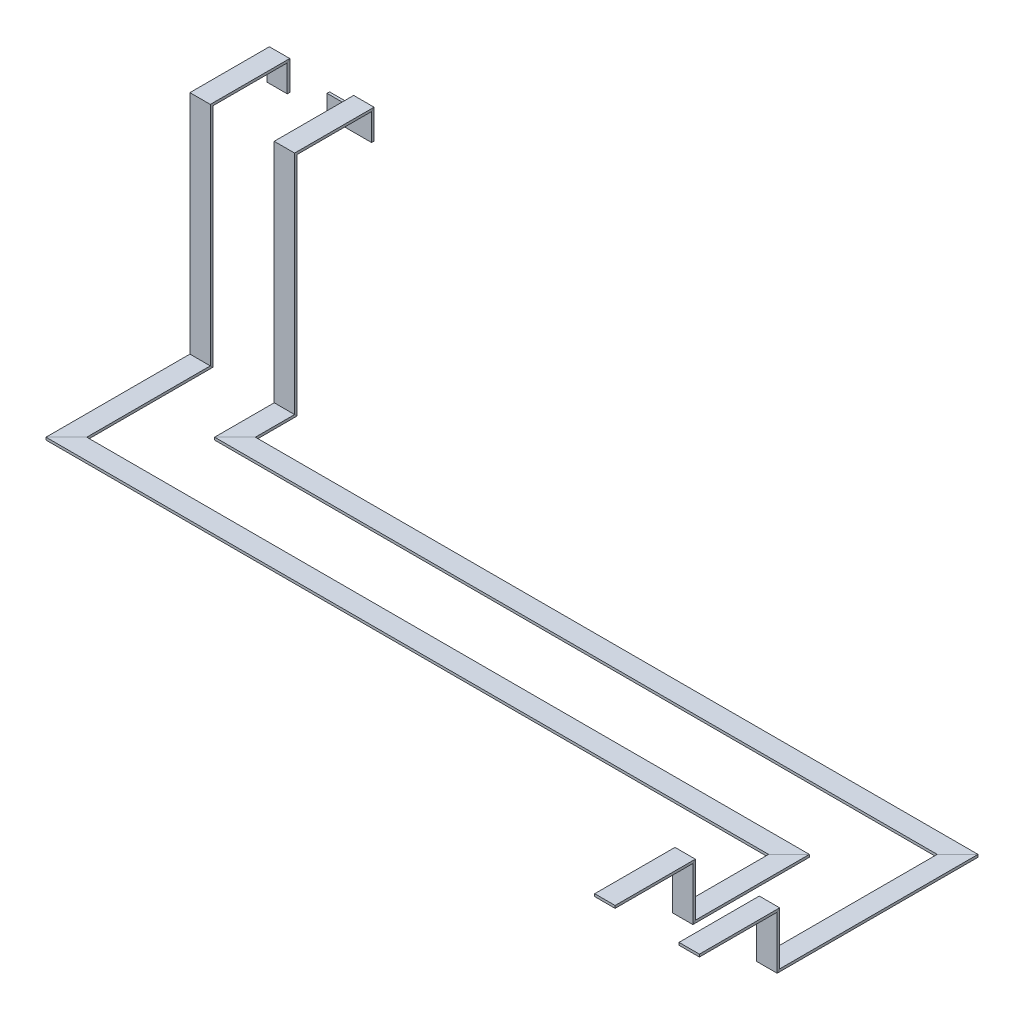
SolidWorks part; units mm, degrees
ref_plane "Alzado" through (0, 0, 0) normal (0, 0, 1) x (1, 0, 0)
ref_plane "Planta" through (0, 0, 0) normal (0, 1, 0) x (1, 0, 0)
ref_plane "Vista lateral" through (0, 0, 0) normal (1, 0, 0) x (0, 0, -1)
sketch "Croquis2" plane through (0, 0, 0) normal (0, 1, 0) x (1, 0, 0)
  line L1 (-25.4, 3.155) -> (25.4, 3.155)
  line L2 (-25.4, 3.155) -> (-25.4, -3.155)
  line L3 (-25.4, -3.155) -> (25.4, -3.155)
  line L4 (25.4, 3.155) -> (25.4, -3.155)
  line L5 (-25.4, 3.155) -> (25.4, -3.155) construction
  line L6 (-25.4, -3.155) -> (25.4, 3.155) construction
  line L7 (184.6, 3.155) -> (235.4, 3.155)
  line L8 (184.6, 3.155) -> (184.6, -3.155)
  line L9 (184.6, -3.155) -> (235.4, -3.155)
  line L10 (235.4, 3.155) -> (235.4, -3.155)
  line L11 (184.6, 3.155) -> (235.4, -3.155) construction
  line L12 (184.6, -3.155) -> (235.4, 3.155) construction
  point P0 (0, 0)
  point P6 (210, 0)
  dimension "D1" = 50.8
  dimension "D2" = 6.31
  dimension "D3" = 210
  dimension "D4" = 50.8
  dimension "D5" = 6.31
sketch3d "Croquis3D1"
  line L0 (0, 0, 0) -> (0, -567.24, 0)
  line L1 (0, -567.24, 0) -> (0, -567.24, 336.2)
  line L2 (0, -567.24, 336.2) -> (1800, -567.24, 336.2)
  line L3 (1800, -567.24, 336.2) -> (1800, -567.24, 598)
  line L4 (-25.4, 0, 0) -> (-25.4, -383.9185, 0) construction
  line L5 (-25.4, 0, -3.155) -> (-25.4, 0, 3.155) construction
  line L6 (-25.4, -383.9185, 0) -> (-25.4, -383.9185, 653.2834) construction
  line L7 (1800, -567.24, 598) -> (1800, -435.4728, 598)
  line L8 (1800, -435.4728, 598) -> (1800, -435.4728, 794.7829)
  dimension "D1" = 567.24
  dimension "D2" = 336.2
  dimension "D3" = 1800
  dimension "D4" = 261.8
  dimension "D5" = 131.7672
  dimension "D6" = 196.7829
sweep "Barrer1" add profiles "Croquis2" path "Croquis3D1"
sketch "Croquis3" plane through (0, 0, -3.155) normal (0, 0, -1) x (-1, 0, 0)
  line L0 (-235.4, 0) -> (-235.4, -6.31)
  line L1 (-235.4, 0) -> (-235.4, -570.395) construction
  line L2 (-235.4, -6.31) -> (-184.6, -6.31)
  line L3 (-184.6, 0) -> (-184.6, -570.395) construction
  line L4 (-184.6, -6.31) -> (-184.6, 0)
  line L5 (-184.6, 0) -> (-235.4, 0)
  line L7 (-25.4, 0) -> (-25.4, -6.31)
  line L8 (-25.4, 0) -> (-25.4, -570.395) construction
  line L9 (-25.4, -6.31) -> (25.4, -6.31)
  line L10 (25.4, 0) -> (25.4, -570.395) construction
  line L11 (25.4, -6.31) -> (25.4, 0)
  line L12 (-25.4, 0) -> (25.4, 0) construction
  line L13 (25.4, 0) -> (-25.4, 0)
  dimension "D1" = 6.31
  dimension "D2" = 6.31
sketch3d "Croquis3D2"
  line L0 (25.4, -3.155, -3.155) -> (-0.201, -3.155, -3.155) construction
  line L1 (25.4, 0, -3.155) -> (25.4, -6.31, -3.155) construction
  line L2 (-0.201, -3.155, -3.155) -> (-0.201, -5.2746, -3.155) construction
  line L3 (-0.201, -3.155, -3.155) -> (-0.201, -3.155, -191.675)
  line L4 (-0.201, -3.155, -191.675) -> (-0.201, -73.155, -191.675)
  dimension "D1" = 188.52
  dimension "D2" = 70
sweep "Barrer4" add profiles "Croquis3" path "Croquis3D2"
sketch "Croquis4" plane through (0, 0, -194.83) normal (0, 0, -1) x (-1, 0, 0)
  line L0 (-184.6, 0) -> (-184.6, -73.155)
  line L1 (-184.6, -73.155) -> (-124.6, -73.155)
  line L2 (-124.6, -73.155) -> (-124.6, 0)
  line L3 (-124.6, 0) -> (-184.6, 0)
  dimension "D1" = 60
sketch "Croquis6" plane through (0, -432.3178, 0) normal (0, 1, 0) x (1, 0, 0)
  circle A0 centre (1285.7, -1260.295) radius 4.75
  circle A1 centre (1495.7, -1260.295) radius 4.75
sketch "Croquis7" plane through (184.6, 0, 0) normal (-1, 0, 0) x (0, 0, 1)
  line L0 (-194.83, -73.155) -> (-188.52, -73.155)
  line L1 (-188.52, -73.155) -> (-188.52, -22.355)
  line L2 (-188.52, -6.31) -> (-188.52, -73.155) construction
  line L3 (-188.52, -22.355) -> (-194.83, -22.355)
  line L4 (-194.83, -22.355) -> (-194.83, -73.155)
  dimension "D1" = 50.8
extrude "Saliente-Extruir1" add sketch "Croquis7" along normal blind 60
